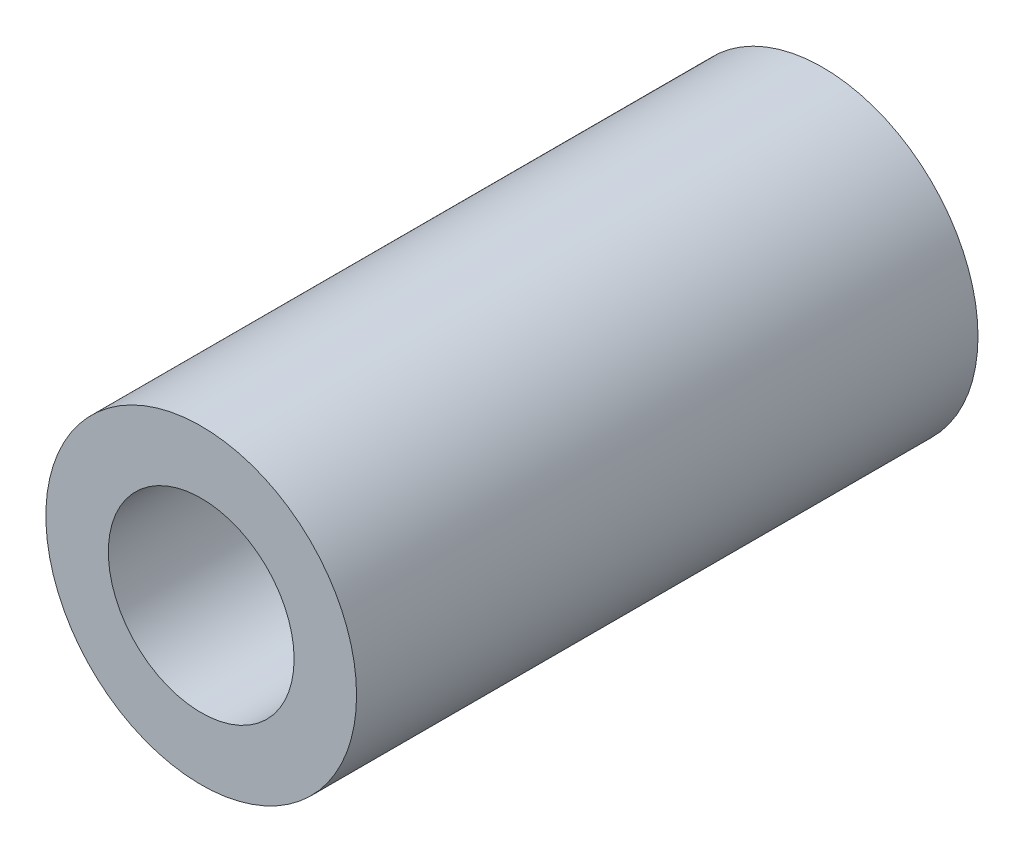
SolidWorks part; units mm, degrees
ref_plane "Front Plane" through (0, 0, 0) normal (0, 0, 1) x (1, 0, 0)
ref_plane "Top Plane" through (0, 0, 0) normal (0, 1, 0) x (1, 0, 0)
ref_plane "Right Plane" through (0, 0, 0) normal (1, 0, 0) x (0, 0, -1)
sketch "Sketch1" plane through (0, 0, 0) normal (0, 0, 1) x (1, 0, 0)
  circle A0 centre (0, 0) radius 3.175
  circle A1 centre (0, 0) radius 1.8986
  dimension "D1" = 6.35
  dimension "D2" = 3.7973
extrude "Boss-Extrude1" add sketch "Sketch1" along normal blind 12.7
